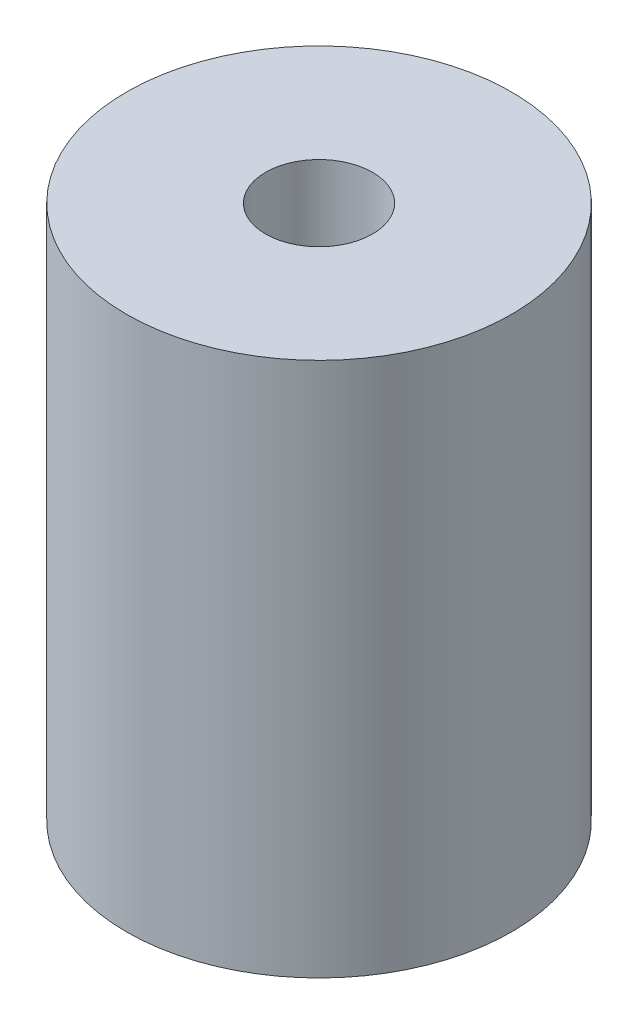
SolidWorks part; units mm, degrees
ref_plane "Front Plane" through (0, 0, 0) normal (0, 0, 1) x (1, 0, 0)
ref_plane "Top Plane" through (0, 0, 0) normal (0, 1, 0) x (1, 0, 0)
ref_plane "Right Plane" through (0, 0, 0) normal (1, 0, 0) x (0, 0, -1)
sketch "Sketch1" plane through (0, 0, 0) normal (0, 1, 0) x (1, 0, 0)
  circle A0 centre (0, 0) radius 9
  circle A1 centre (0, 0) radius 2.5
  dimension "D1" = 18
extrude "Boss-Extrude1" add sketch "Sketch1" along normal blind 25
sketch "Sketch2" plane through (0, 0, 0) normal (0, -1, 0) x (1, 0, 0)
  circle A0 centre (0, 0) radius 4
  dimension "D1" = 8
extrude "Cut-Extrude1" cut sketch "Sketch2" against normal blind 10
